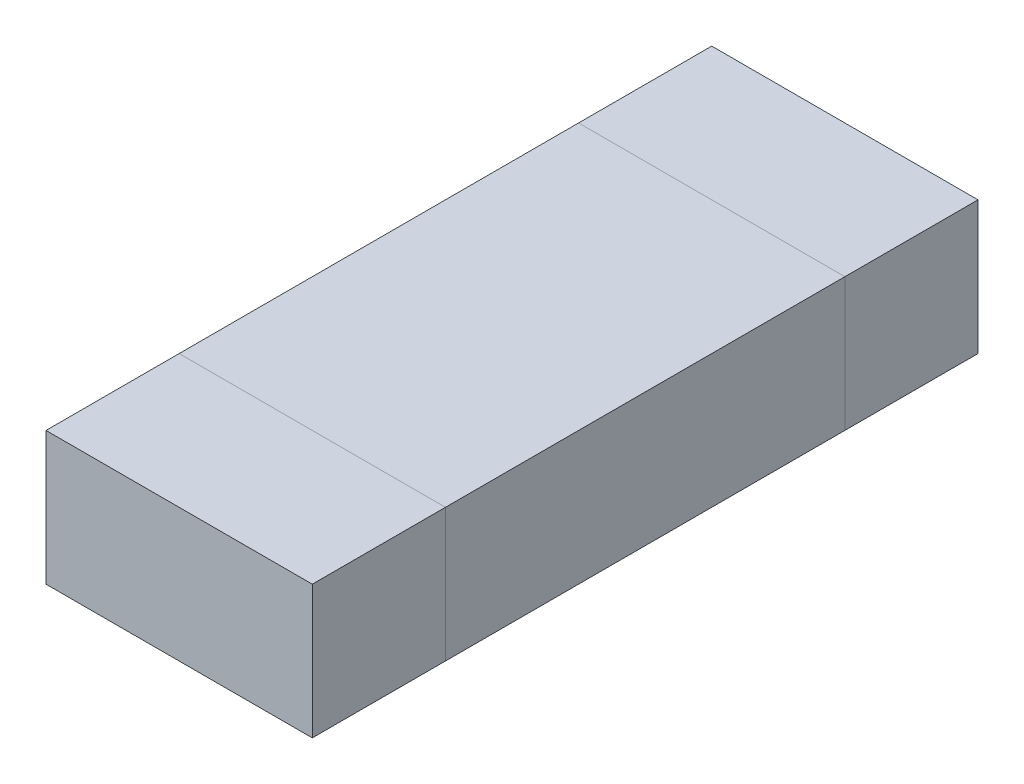
SolidWorks part; units mm, degrees
ref_plane "Front Plane" through (0, 0, 0) normal (0, 0, 1) x (1, 0, 0)
ref_plane "Top Plane" through (0, 0, 0) normal (0, 1, 0) x (1, 0, 0)
ref_plane "Right Plane" through (0, 0, 0) normal (1, 0, 0) x (0, 0, -1)
sketch "Sketch1" plane through (0, 0, 0) normal (0, 1, 0) x (1, 0, 0)
  line L1 (-0.4, 0.6) -> (0.4, 0.6)
  line L2 (-0.4, 0.6) -> (-0.4, -0.6)
  line L3 (-0.4, -0.6) -> (0.4, -0.6)
  line L4 (0.4, 0.6) -> (0.4, -0.6)
  line L5 (-0.4, 0.6) -> (0.4, -0.6) construction
  line L6 (-0.4, -0.6) -> (0.4, 0.6) construction
  point P0 (0, 0)
  dimension "D1" = 1.2
  dimension "D2" = 0.8
extrude "MB" add sketch "Sketch1" along normal blind 0.4
sketch "Sketch2" plane through (0, 0, 0.6) normal (0, 0, 1) x (1, 0, 0)
  line L4 (-0.4, 0) -> (0.4, 0)
  line L5 (0.4, 0) -> (0.4, 0.4)
  line L6 (0.4, 0.4) -> (-0.4, 0.4)
  line L7 (-0.4, 0.4) -> (-0.4, 0)
  line L8 (-0.4, 0) -> (0.4, 0)
  line L9 (0.4, 0) -> (0.4, 0.4)
  line L10 (0.4, 0.4) -> (-0.4, 0.4)
  line L11 (-0.4, 0.4) -> (-0.4, 0)
  dimension "D1" = 0
extrude "SB L" add sketch "Sketch2" along normal blind 0.4 separate body
sketch "Sketch3" plane through (0, 0, -0.6) normal (0, 0, -1) x (-1, 0, 0)
  line L4 (-0.4, 0) -> (0.4, 0)
  line L5 (0.4, 0) -> (0.4, 0.4)
  line L6 (0.4, 0.4) -> (-0.4, 0.4)
  line L7 (-0.4, 0.4) -> (-0.4, 0)
  line L8 (-0.4, 0) -> (0.4, 0)
  line L9 (0.4, 0) -> (0.4, 0.4)
  line L10 (0.4, 0.4) -> (-0.4, 0.4)
  line L11 (-0.4, 0.4) -> (-0.4, 0)
  dimension "D1" = 0
extrude "SB R" add sketch "Sketch3" along normal blind 0.4 separate body
